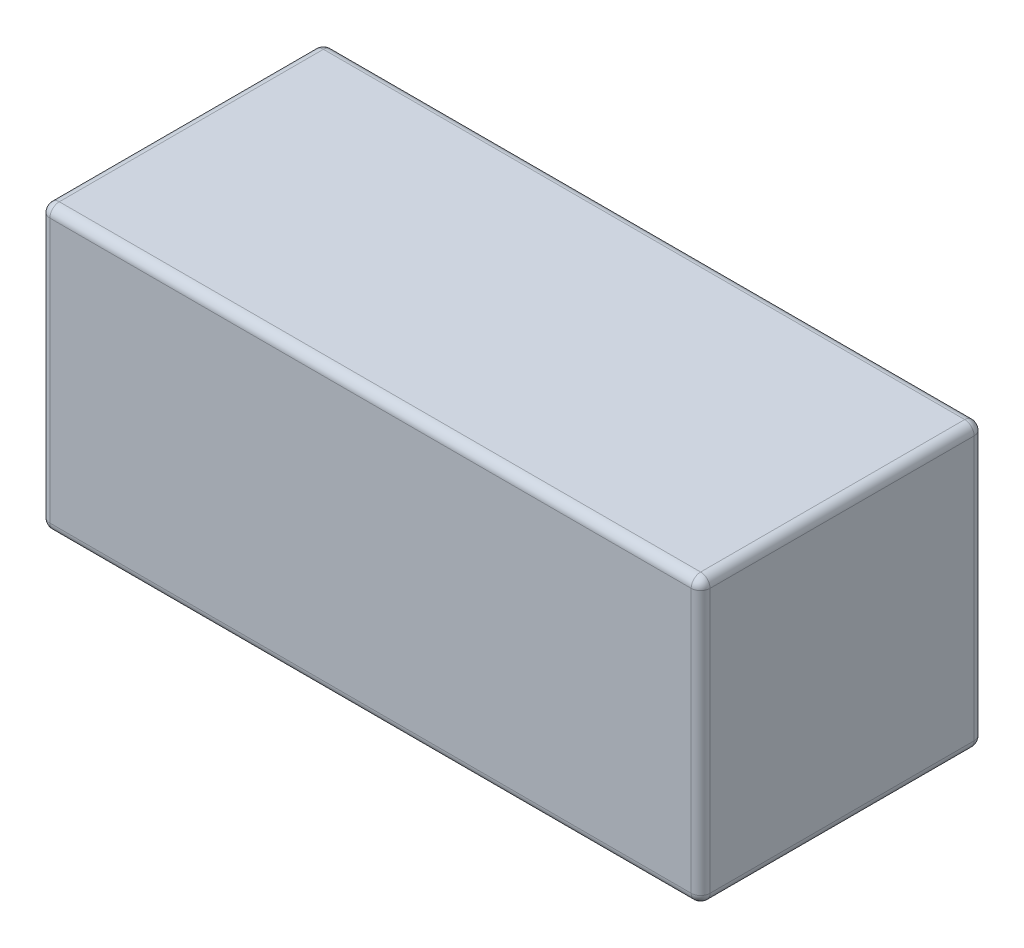
SolidWorks part; units mm, degrees
material "ABS"
ref_plane "Front Plane" through (0, 0, 0) normal (0, 0, 1) x (1, 0, 0)
ref_plane "Top Plane" through (0, 0, 0) normal (0, 1, 0) x (1, 0, 0)
ref_plane "Right Plane" through (0, 0, 0) normal (1, 0, 0) x (0, 0, -1)
sketch "Sketch1" plane through (0, 0, 0) normal (0, 1, 0) x (1, 0, 0)
  line L1 (-31.3876, 16.3761) -> (38.6124, 16.3761)
  line L2 (-31.3876, 16.3761) -> (-31.3876, -13.6239)
  line L3 (-31.3876, -13.6239) -> (38.6124, -13.6239)
  line L4 (38.6124, 16.3761) -> (38.6124, -13.6239)
  dimension "D1" = 70
  dimension "D2" = 30
extrude "Boss-Extrude1" add sketch "Sketch1" along normal blind 30
fillet "Fillet1" radius 1 12 edges at (-31.3876, 15, -16.3761) (3.6124, 0, -16.3761) (38.6124, 0, -1.3761) (-31.3876, 0, -1.3761) (3.6124, 0, 13.6239) (38.6124, 30, -1.3761) (38.6124, 15, -16.3761) (38.6124, 15, 13.6239) (-31.3876, 15, 13.6239) (3.6124, 30, -16.3761) (-31.3876, 30, -1.3761) (3.6124, 30, 13.6239)
